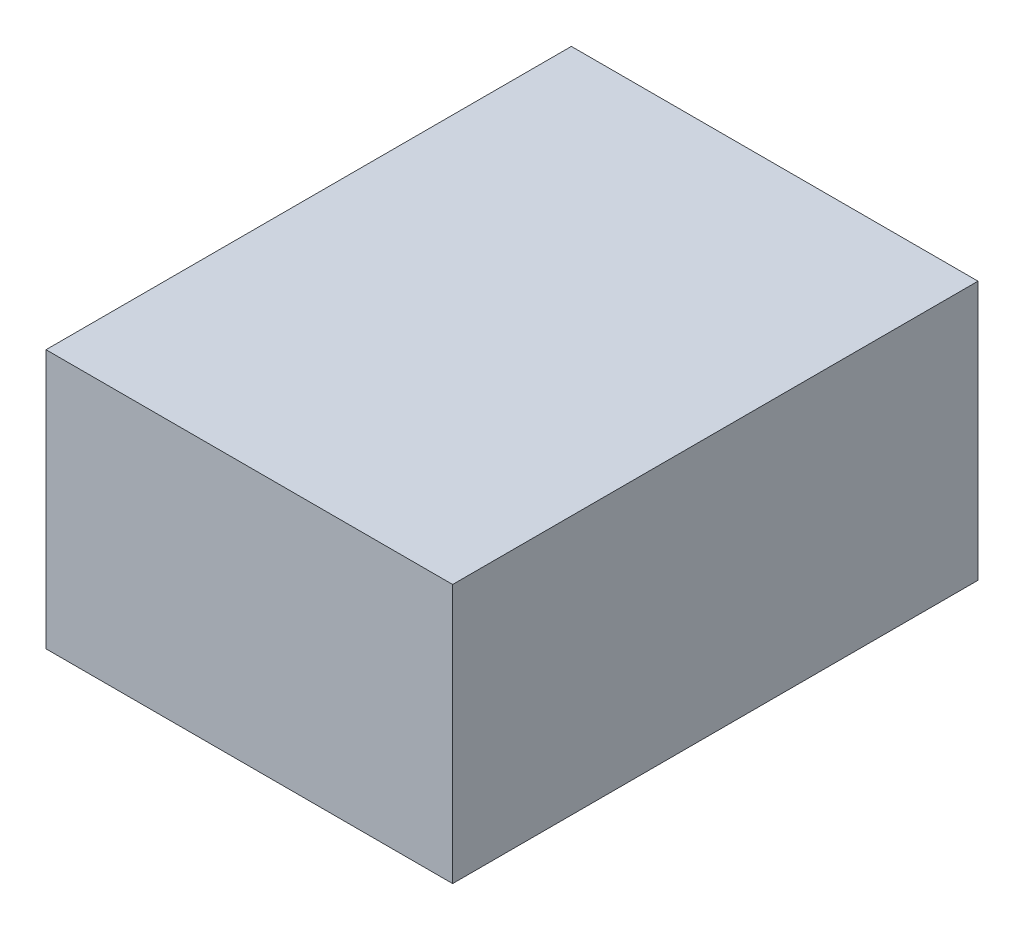
SolidWorks part; units mm, degrees
ref_plane "Front Plane" through (0, 0, 0) normal (0, 0, 1) x (1, 0, 0)
ref_plane "Top Plane" through (0, 0, 0) normal (0, 1, 0) x (1, 0, 0)
ref_plane "Right Plane" through (0, 0, 0) normal (1, 0, 0) x (0, 0, -1)
sketch "Sketch1" plane through (0, 0, 0) normal (0, 0, 1) x (1, 0, 0)
  line L1 (3100, -1975) -> (-3100, -1975)
  line L2 (3100, -1975) -> (3100, 1975)
  line L3 (3100, 1975) -> (-3100, 1975)
  line L4 (-3100, -1975) -> (-3100, 1975)
  line L5 (3100, -1975) -> (-3100, 1975) construction
  line L6 (3100, 1975) -> (-3100, -1975) construction
  point P0 (0, 0)
  dimension "D1" = 6200
  dimension "D2" = 3950
extrude "Boss-Extrude1" add sketch "Sketch1" along normal blind 8000
sketch "Sketch2" plane through (0, 0, 0) normal (0, 0, 1) x (1, 0, 0)
  line L0 (-3100, -1975) -> (3100, -1975) construction
  line L2 (-2500, -1875) -> (2500, -1875)
  line L3 (-2500, -1875) -> (-2500, 1625)
  line L4 (-2500, 1625) -> (2500, 1625)
  line L5 (2500, -1875) -> (2500, 1625)
  line L6 (-3100, 1975) -> (-3100, -1975) construction
  dimension "D1" = 100
  dimension "D2" = 600
  dimension "D3" = 3500
  dimension "D4" = 5000
extrude "Cut-Extrude3" cut sketch "Sketch2" along normal blind 6200
sketch "Sketch4" plane through (0, 0, 0) normal (0, 0, 1) x (1, 0, 0)
  line L0 (2500, -1875) -> (2500, 1625) construction
  line L1 (3000, -1875) -> (2550, -1875)
  line L2 (3000, -1875) -> (3000, 1875)
  line L3 (3000, 1875) -> (2550, 1875)
  line L4 (2550, -1875) -> (2550, 1875)
  line L5 (3100, 1975) -> (-3100, 1975) construction
  line L7 (-3100, 1975) -> (-3100, -1975) construction
  line L8 (-2550, -1882.0855) -> (-3000, -1882.0855)
  line L9 (-2550, -1882.0855) -> (-2550, 1867.9145)
  line L10 (-2550, 1867.9145) -> (-3000, 1867.9145)
  line L11 (-3000, -1882.0855) -> (-3000, 1867.9145)
  dimension "D1" = 450
  dimension "D2" = 50
  dimension "D3" = 3750
  dimension "D4" = 100
  dimension "D5" = 3750
  dimension "D6" = 450
  dimension "D7" = 100
extrude "Cut-Extrude5" cut sketch "Sketch4" along normal blind 6200 contours L10 L11 L8 L9 | L3 L4 L1 L2
sketch "Sketch5" plane through (0, 0, 0) normal (0, 0, -1) x (-1, 0, 0)
  line L0 (-2500, 1625) -> (2500, 1625) construction
  line L1 (-2500, 1875) -> (2500, 1875)
  line L2 (-2500, 1875) -> (-2500, 1675)
  line L3 (-2500, 1675) -> (2500, 1675)
  line L4 (2500, 1875) -> (2500, 1675)
  line L5 (3100, 1975) -> (3100, -1975) construction
  dimension "D1" = 200
  dimension "D2" = 50
  dimension "D3" = 5000
  dimension "D4" = 600
extrude "Cut-Extrude6" cut sketch "Sketch5" against normal blind 8000
sketch "Sketch6" plane through (0, 0, 8000) normal (0, 0, 1) x (1, 0, 0)
  line L1 (-3000, -1882.0855) -> (3000, -1882.0855)
  line L2 (-3000, -1882.0855) -> (-3000, 1875)
  line L3 (-3000, 1875) -> (3000, 1875)
  line L4 (3000, -1882.0855) -> (3000, 1875)
extrude "Cut-Extrude8" cut sketch "Sketch6" against normal blind 1600
sketch "Sketch7" plane through (0, 0, 8000) normal (0, 0, 1) x (1, 0, 0)
  line L1 (-3100, -1975) -> (3100, -1975)
  line L2 (-3100, -1975) -> (-3100, 1975)
  line L3 (-3100, 1975) -> (3100, 1975)
  line L4 (3100, -1975) -> (3100, 1975)
extrude "Boss-Extrude2" add sketch "Sketch7" along normal blind 10
